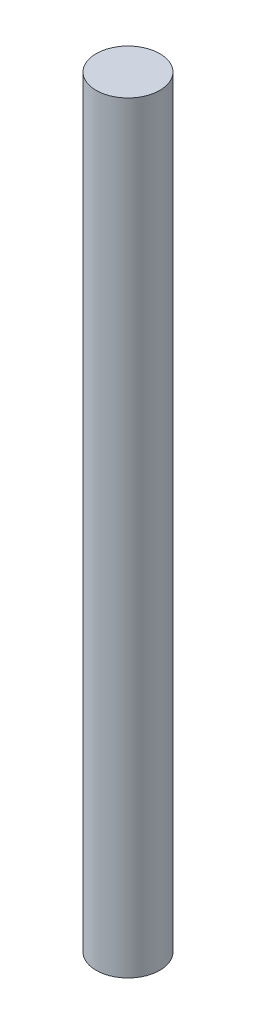
SolidWorks part; units mm, degrees
ref_plane "Alzado" through (0, 0, 0) normal (0, 0, 1) x (1, 0, 0)
ref_plane "Planta" through (0, 0, 0) normal (0, 1, 0) x (1, 0, 0)
ref_plane "Vista lateral" through (0, 0, 0) normal (1, 0, 0) x (0, 0, -1)
sketch "Croquis5" plane through (0, 0, 0) normal (0, 1, 0) x (1, 0, 0)
  circle A0 centre (0, 0) radius 3.175
  dimension "D1" = 6.35
extrude "Saliente-Extruir2" add sketch "Croquis5" along normal blind 76
